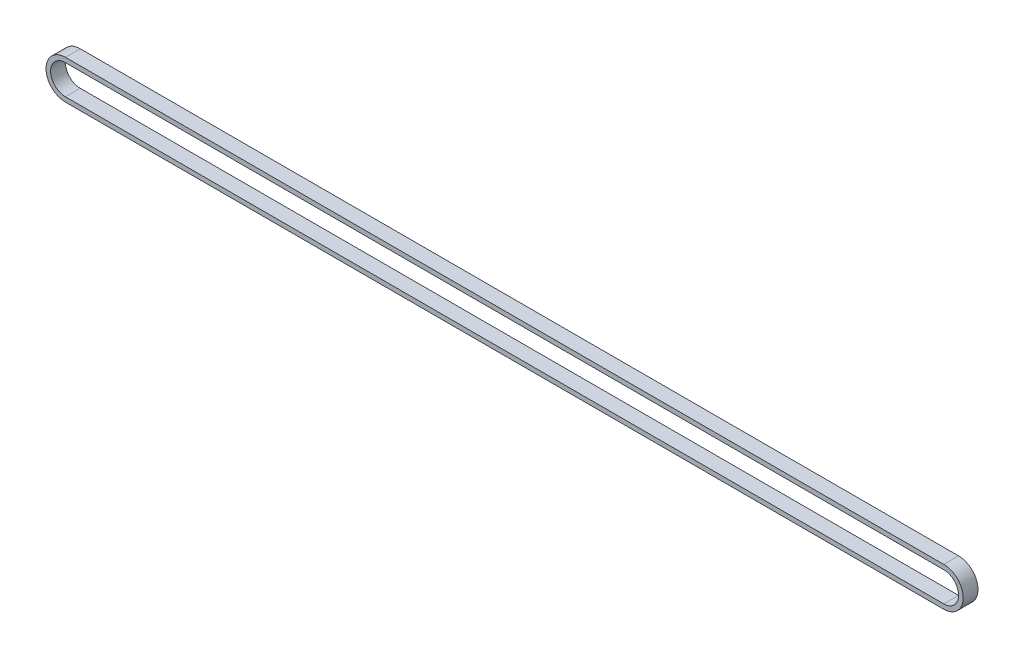
SolidWorks part; units mm, degrees
ref_plane "Front Plane" through (0, 0, 0) normal (0, 0, 1) x (1, 0, 0)
ref_plane "Top Plane" through (0, 0, 0) normal (0, 1, 0) x (1, 0, 0)
ref_plane "Right Plane" through (0, 0, 0) normal (1, 0, 0) x (0, 0, -1)
sketch "Sketch1" plane through (0, 0, 0) normal (0, 0, 1) x (1, 0, 0)
  line L0 (0, 21) -> (950, 21)
  line L1 (950, -21) -> (0, -21)
  line L2 (0, 16) -> (950, 16)
  line L3 (950, -16) -> (0, -16)
  arc A0 (0, 21) -> (0, -21) centre (0, 0) ccw
  arc A1 (950, -21) -> (950, 21) centre (950, 0) ccw
  arc A2 (950, -16) -> (950, 16) centre (950, 0) ccw
  arc A3 (0, 16) -> (0, -16) centre (0, 0) ccw
  dimension "D1" = 42
  dimension "D3" = 950
  dimension "D4" = 5
  dimension "D2" = 2
extrude "Boss-Extrude1" add sketch "Sketch1" along normal mid plane 16
